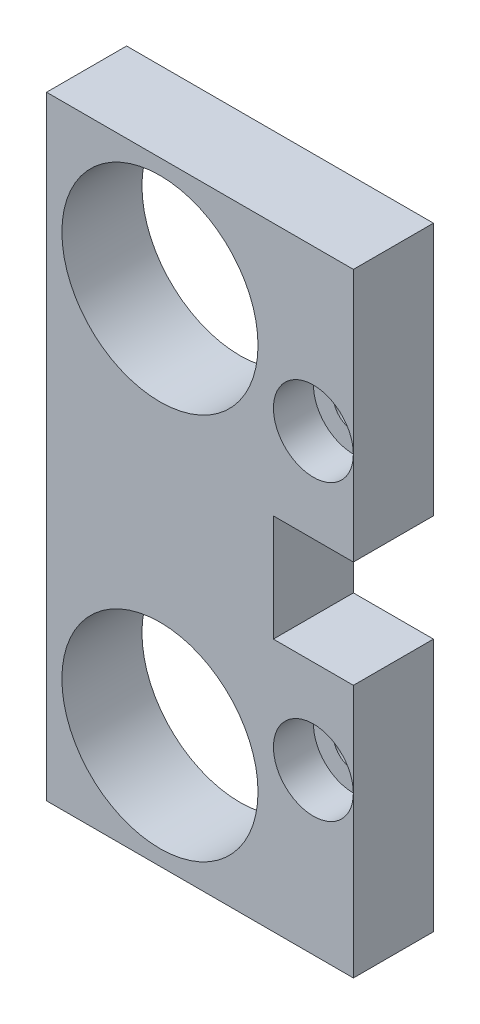
SolidWorks part; units mm, degrees
ref_plane "Plan de face" through (0, 0, 0) normal (0, 0, 1) x (1, 0, 0)
ref_plane "Plan de dessus" through (0, 0, 0) normal (0, 1, 0) x (1, 0, 0)
ref_plane "Plan de droite" through (0, 0, 0) normal (1, 0, 0) x (0, 0, -1)
sketch "Esquisse1" plane through (0, 0, 0) normal (0, 0, 1) x (1, 0, 0)
  line L1 (0, 46) -> (50, 46)
  line L2 (0, 46) -> (0, 0)
  line L3 (0, 0) -> (50, 0)
  line L4 (50, 46) -> (50, 0)
  dimension "D1" = 50
  dimension "D2" = 46
  dimension "D3" = 0
  dimension "D4" = 0
extrude "Boss.-Extru.2" add sketch "Esquisse1" along normal blind 6 contours L1 L4 L3 L2
sketch "Esquisse2" plane through (0, 0, 6) normal (0, 0, 1) x (1, 0, 0)
  line L0 (27, 46) -> (27, 0) construction
  line L1 (27, 46) -> (0, 46)
  line L2 (0, 0) -> (27, 0)
  line L3 (50, 46) -> (50, 0) construction
  line L4 (0, 46) -> (50, 46) construction
  line L5 (0, 0) -> (50, 0) construction
  line L8 (0, 0) -> (0, 46)
  line L10 (27, 46) -> (27, 0)
  dimension "D1" = 23
extrude "Enlèv. mat.-Extru.1" cut sketch "Esquisse2" against normal blind 6
sketch "Esquisse3" plane through (0, 0, 6) normal (0, 0, 1) x (1, 0, 0)
  line L0 (38.5, 46) -> (38.5, 0) construction
  line L1 (27, 46) -> (50, 46) construction
  line L2 (27, 0) -> (50, 0) construction
  line L3 (50, 46) -> (50, 0) construction
  line L4 (44, 46) -> (44, 0) construction
  line L5 (27, 46) -> (50, 46) construction
  line L6 (27, 0) -> (50, 0) construction
  line L7 (32.75, 0) -> (32.75, 46) construction
  circle A0 centre (35.5, 37.5) radius 7.35
  circle A1 centre (35.5, 8.5) radius 7.35
  dimension "D2" = 14.7
  dimension "D3" = 14.7
  dimension "D5" = 8.5
  dimension "D8" = 8.5
  dimension "D1" = 11.5
  dimension "D4" = 6
  dimension "D6" = 8.5
  dimension "D7" = 8.5
  dimension "D9" = 5.75
extrude "Enlèv. mat.-Extru.2" cut sketch "Esquisse3" against normal blind 6
sketch "Esquisse4" plane through (0, 0, 6) normal (0, 0, 1) x (1, 0, 0)
  line L0 (44, 46) -> (44, 0) construction
  line L1 (27, 46) -> (50, 46) construction
  line L2 (27, 0) -> (50, 0) construction
  line L3 (50, 46) -> (50, 0) construction
  circle A1 centre (47, 34) radius 1.5
  circle A2 centre (47, 12) radius 1.5
  dimension "D1" = 6
  dimension "D2" = 3
  dimension "D3" = 3
  dimension "D4" = 3
  dimension "D5" = 3
  dimension "D6" = 12
  dimension "D7" = 12
extrude "Enlèv. mat.-Extru.3" cut sketch "Esquisse4" against normal blind 6
sketch "Esquisse5" plane through (0, 0, 6) normal (0, 0, 1) x (1, 0, 0)
  circle A0 centre (47, 12) radius 2.995
  circle A1 centre (47, 34) radius 2.995
  dimension "D1" = 5.99
  dimension "D2" = 5.99
extrude "Enlèv. mat.-Extru.5" cut sketch "Esquisse5" against normal blind 3
sketch "Esquisse6" plane through (0, 0, 6) normal (0, 0, 1) x (1, 0, 0)
  line L0 (50, 46) -> (50, 0) construction
  line L1 (50, 27) -> (44, 27)
  line L2 (50, 27) -> (50, 19)
  line L3 (50, 19) -> (44, 19)
  line L4 (44, 27) -> (44, 19)
  line L5 (27, 46) -> (50, 46) construction
  line L6 (27, 0) -> (50, 0) construction
  circle A0 centre (47, 34) radius 1.5 construction
  dimension "D1" = 6
  dimension "D2" = 19
  dimension "D3" = 19
  dimension "D4" = 8
  dimension "D5" = 7
extrude "Enlèv. mat.-Extru.6" cut sketch "Esquisse6" against normal blind 6
